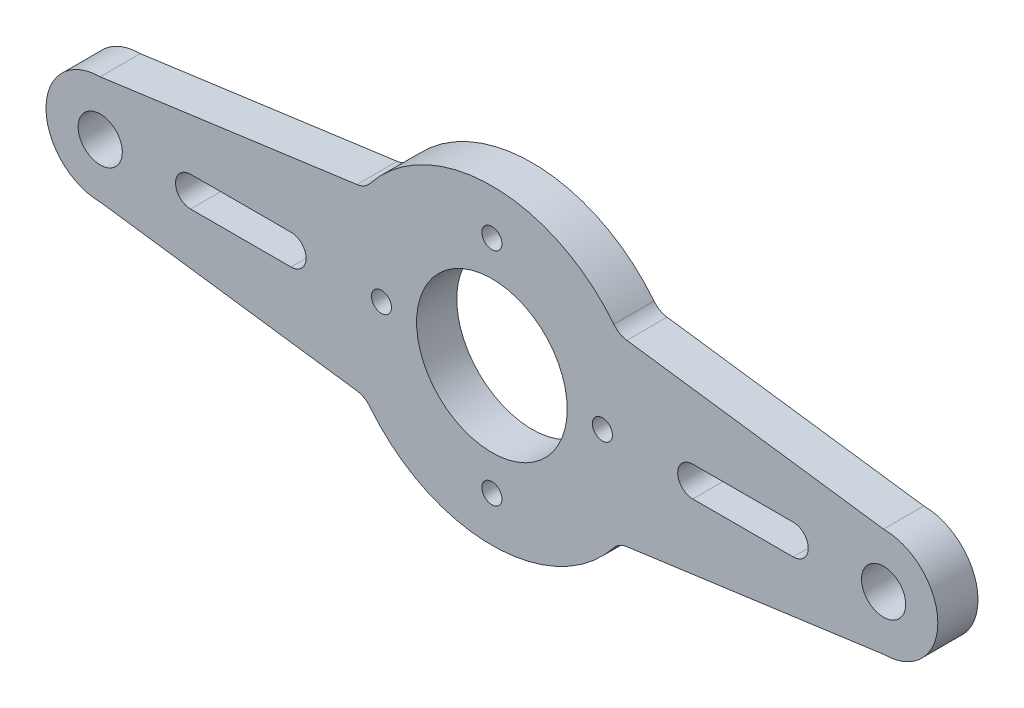
SolidWorks part; units mm, degrees
ref_plane "Front Plane" through (0, 0, 0) normal (0, 0, 1) x (1, 0, 0)
ref_plane "Top Plane" through (0, 0, 0) normal (0, 1, 0) x (1, 0, 0)
ref_plane "Right Plane" through (0, 0, 0) normal (1, 0, 0) x (0, 0, -1)
sketch "Sketch1" plane through (0, 0, 0) normal (0, 0, 1) x (1, 0, 0)
  line L0 (-19.5, 0) -> (19.5, 0) construction
  line L1 (-19.5, 2.7) -> (-6.3062, 4.505)
  line L2 (-19.5, -2.7) -> (-6.3062, -4.505)
  line L3 (-10, 0) -> (-15, 0) construction
  line L4 (-10, -0.75) -> (-15, -0.75)
  line L5 (-10, 0.75) -> (-15, 0.75)
  line L6 (0, 0) -> (0, 14.7258) construction
  line L7 (10, 0) -> (15, 0) construction
  line L8 (10, -0.75) -> (15, -0.75)
  line L9 (10, 0.75) -> (15, 0.75)
  line L10 (19.5, -2.7) -> (6.3062, -4.505)
  line L11 (19.5, 2.7) -> (6.3062, 4.505)
  arc A0 (-6.3062, -4.505) -> (6.3062, -4.505) centre (0, 0) ccw
  arc A1 (-19.5, 2.7) -> (-19.5, -2.7) centre (-19.5, 0) ccw
  circle A2 centre (-19.5, 0) radius 1.1
  arc A3 (-10, -0.75) -> (-10, 0.75) centre (-10, 0) ccw
  arc A4 (-15, 0.75) -> (-15, -0.75) centre (-15, 0) ccw
  arc A5 (10, -0.75) -> (10, 0.75) centre (10, 0) cw
  arc A6 (15, 0.75) -> (15, -0.75) centre (15, 0) cw
  circle A7 centre (19.5, 0) radius 1.1
  arc A8 (19.5, 2.7) -> (19.5, -2.7) centre (19.5, 0) cw
  arc A9 (6.3062, 4.505) -> (-6.3062, 4.505) centre (0, 0) ccw
  circle A10 centre (0, 0) radius 3.75
  point P5 (0, 0)
  point P13 (-12.5, 0)
  point P20 (12.5, 0)
  dimension "D1" = 15.5
  dimension "D3" = 5.4
  dimension "D5" = 2.2
  dimension "D8" = 10
  dimension "D9" = 7.5
  dimension "D2" = 39
  dimension "D4" = 7.79
  dimension "D6" = 1.5
  dimension "D7" = 5
extrude "Boss-Extrude1" add sketch "Sketch1" along normal blind 2
hole_wizard "Ø1.0mm Dowel Hole1" positions "Sketch2" profile "Sketch3" hole size "Ø1.0" standard "ANSI Metric" end condition through all
sketch "Sketch2" plane through (0, 0, 2) normal (0, 0, 1) x (1, 0, 0)
  circle A0 centre (0, 0) radius 5.5 construction
  point P5 (0, 5.5)
  point P7 (5.5, 0)
  point P9 (0, -5.5)
  point P11 (-5.5, 0)
  dimension "D1" = 11
sketch "Sketch3" plane through (-5.5, 0, 2) normal (1, 0, 0) x (0, -1, 0)
  line L0 (0, 0) -> (0, 2)
  line L1 (0, 2) -> (0.5, 2)
  line L2 (0.5, 2) -> (0.5, 0)
  line L5 (0.5, 0) -> (0, 0)
  line L11 (0, -6.35) -> (0, 107.95) construction
  dimension "Thru Hole Dia." = 1
  dimension "Thru Hole Depth" = 2
fillet "Fillet1" radius 1 4 edges at (-6.3062, 4.505, 1) (-6.3062, -4.505, 1) (6.3062, -4.505, 1) (6.3062, 4.505, 1)
